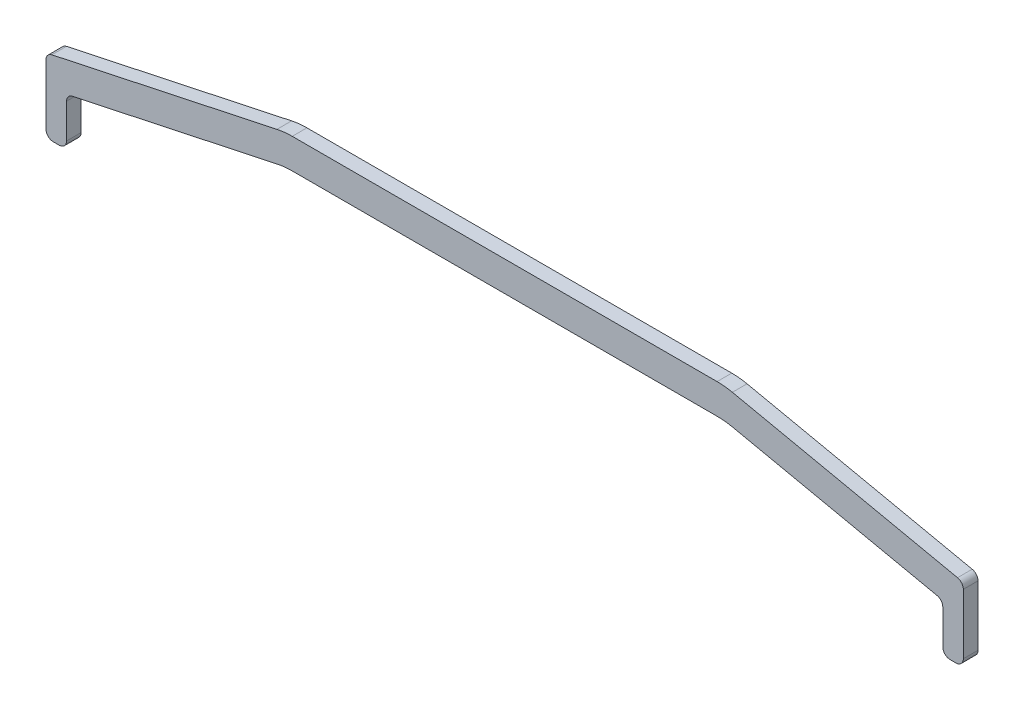
SolidWorks part; units mm, degrees
ref_plane "Alzado" through (0, 0, 0) normal (0, 0, 1) x (1, 0, 0)
ref_plane "Planta" through (0, 0, 0) normal (0, 1, 0) x (1, 0, 0)
ref_plane "Vista lateral" through (0, 0, 0) normal (1, 0, 0) x (0, 0, -1)
sketch "Croquis1" plane through (0, 0, 0) normal (0, 0, 1) x (1, 0, 0)
  line L0 (-27.4687, 15.9863) -> (30.4223, 15.9863)
  line L1 (-27.4687, 11.8963) -> (30.4223, 11.8963)
  line L2 (-29.5545, 15.7663) -> (-60.2318, 9.2238)
  line L3 (-61.0232, 8.2458) -> (-61.0232, 0.055)
  line L4 (-60.0232, -0.945) -> (-59.2232, -0.945)
  line L5 (-58.2232, 0.055) -> (-58.2232, 4.753)
  line L6 (-57.4318, 5.731) -> (-29.5545, 11.6764)
  line L8 (60.3854, 5.731) -> (32.5081, 11.6764)
  line L9 (61.1768, 0.055) -> (61.1768, 4.753)
  line L10 (62.9768, -0.945) -> (62.1768, -0.945)
  line L11 (63.9768, 8.2458) -> (63.9768, 0.055)
  line L12 (32.5081, 15.7663) -> (63.1854, 9.2238)
  line L13 (31.4768, 11.8963) -> (-28.5232, 11.8963)
  line L14 (31.4768, 15.9863) -> (-28.5232, 15.9863)
  arc A0 (60.3854, 5.731) -> (61.1768, 4.753) centre (60.1768, 4.753) cw
  arc A1 (63.1854, 9.2238) -> (63.9768, 8.2458) centre (62.9768, 8.2458) cw
  arc A2 (63.9768, 0.055) -> (62.9768, -0.945) centre (62.9768, 0.055) cw
  arc A3 (62.1768, -0.945) -> (61.1768, 0.055) centre (62.1768, 0.055) cw
  arc A4 (-60.2318, 9.2238) -> (-61.0232, 8.2458) centre (-60.0232, 8.2458) ccw
  arc A5 (-57.4318, 5.731) -> (-58.2232, 4.753) centre (-57.2232, 4.753) ccw
  arc A6 (-58.2232, 0.055) -> (-59.2232, -0.945) centre (-59.2232, 0.055) cw
  arc A7 (-60.0232, -0.945) -> (-61.0232, 0.055) centre (-60.0232, 0.055) cw
  arc A8 (-27.4687, 15.9863) -> (-29.5545, 15.7663) centre (-27.4687, 5.9863) ccw
  arc A9 (-27.4687, 11.8963) -> (-29.5545, 11.6764) centre (-27.4687, 1.8963) ccw
  arc A10 (30.4223, 15.9863) -> (32.5081, 15.7663) centre (30.4223, 5.9863) cw
  arc A11 (30.4223, 11.8963) -> (32.5081, 11.6764) centre (30.4223, 1.8963) cw
  point P0 (1.4768, 15.9863)
  point P17 (1.4768, 15.9863)
  dimension "D3" = 1
  dimension "D4" = 10
  dimension "D1" = 60
  dimension "D2" = 60
extrude "Saliente-Extruir1" add sketch "Croquis1" along normal blind 2
